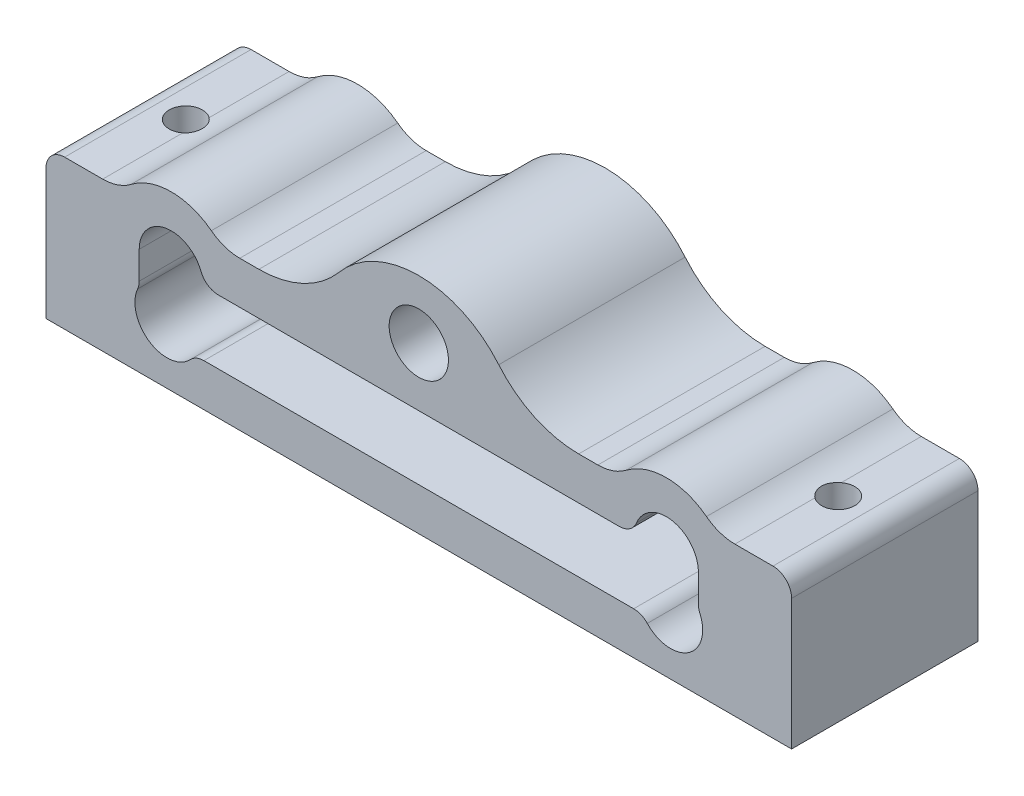
SolidWorks part; units mm, degrees
material "Delrin 2700 NC010, Low Viscosity Acetal Copolymer (SS)"
ref_plane "Front Plane" through (0, 0, 0) normal (0, 0, 1) x (1, 0, 0)
ref_plane "Top Plane" through (0, 0, 0) normal (0, 1, 0) x (1, 0, 0)
ref_plane "Right Plane" through (0, 0, 0) normal (1, 0, 0) x (0, 0, -1)
sketch "Sketch1" plane through (0, 0, 0) normal (0, 0, 1) x (1, 0, 0)
  line L0 (6.35, 5.08) -> (25.4, 5.08)
  line L9 (-25.4, -5.08) -> (25.4, -5.08)
  line L10 (-25.4, -5.08) -> (-25.4, 5.08)
  line L11 (-25.4, 5.08) -> (-6.35, 5.08)
  line L12 (25.4, -5.08) -> (25.4, 5.08)
  line L13 (-19.05, -2.1828) -> (19.05, -2.1828)
  line L14 (-19.05, -2.1828) -> (-19.05, 2.1828)
  line L15 (-19.05, 2.1828) -> (19.05, 2.1828)
  line L16 (19.05, -2.1828) -> (19.05, 2.1828)
  line L19 (-6.35, 5.08) -> (6.35, 5.08)
  point P9 (0, -2.1828)
  point P11 (19.05, 0)
  point P12 (25.4, 0)
  point P17 (0, 5.08)
  point P18 (0, -5.08)
  dimension "D1" = 50.8
  dimension "D2" = 10.16
  dimension "D3" = 38.1
  dimension "D4" = 4.3656
  dimension "D5" = 12.7
extrude "Boss-Extrude1" add sketch "Sketch1" along normal blind 12.7
sketch "Sketch7" plane through (0, 0, 12.7) normal (0, 0, 1) x (1, 0, 0)
  line L0 (19.05, 2.1828) -> (-19.05, 2.1828) construction
  line L1 (25.4, 5.08) -> (-25.4, 5.08) construction
  line L2 (-16.8672, 5.08) -> (-16.8672, 6.6675) construction
  line L3 (-20.2905, 5.08) -> (-13.4439, 5.08)
  circle A0 centre (-16.8672, 2.1828) radius 2.1828 construction
  arc A1 (-13.4439, 5.08) -> (-20.2905, 5.08) centre (-16.8672, 2.1828) ccw
  dimension "D1" = 4.3656
  dimension "D2" = 1.5875
extrude "Boss-Extrude3" add sketch "Sketch7" against normal up to surface (12.7 mm away) up to face at (0, 0, 0)
sketch "Sketch8" plane through (0, 0, 12.7) normal (0, 0, 1) x (1, 0, 0)
  line L0 (19.05, 2.1828) -> (-19.05, 2.1828) construction
  circle A0 centre (-16.8672, 2.1828) radius 2.1828
  dimension "D1" = 4.3656
extrude "Cut-Extrude1" cut sketch "Sketch8" against normal through all
sketch "Sketch11" plane through (0, 0, 12.7) normal (0, 0, 1) x (1, 0, 0)
  line L0 (-15.2693, -2.1828) -> (-19.05, 0) construction
  line L1 (-19.05, -2.1828) -> (19.05, -2.1828) construction
  line L2 (-19.05, 2.1828) -> (-19.05, -2.1828) construction
  circle A0 centre (-17.1596, -1.0914) radius 2.1828
  point P4 (-17.1596, -1.0914)
  dimension "D1" = 4.3656
extrude "Cut-Extrude2" cut sketch "Sketch11" against normal through all
fillet "Fillet1" radius 3.175 1 edges at (-13.4439, 5.08, 6.35)
mirror "Mirror1" about plane through (0, 0, 0) normal (1, 0, 0) of "Cut-Extrude2", "Cut-Extrude1"
mirror "Mirror2" about plane through (0, 0, 0) normal (1, 0, 0) of "Boss-Extrude3"
fillet "Fillet2" radius 3.175 1 edges at (13.4439, 5.08, 6.35)
hole_wizard "#4-40 Tapped Hole1" positions "Sketch2" profile "Sketch3" tap size "#4-40" standard "ANSI Inch" end condition through all
sketch "Sketch2" plane through (0, -5.08, 0) normal (0, -1, 0) x (-1, 0, 0)
  line L0 (-22.225, -6.35) -> (22.225, -6.35) construction
  line L2 (25.4, 0) -> (-25.4, 0) construction
  line L4 (25.4, -12.7) -> (-25.4, -12.7) construction
  point P0 (22.225, -6.35)
  point P2 (-22.225, -6.35)
  point P19 (0, 0)
  point P20 (0, -6.35)
  dimension "D1" = 44.45
  dimension "D2" = 6.35
cosmetic thread "Hole Thread4" parameters "D2"=2.8448
cosmetic thread "Hole Thread5" parameters "D2"=2.8448
sketch "Sketch3" plane through (-22.225, -5.08, 6.35) normal (1, 0, 0) x (0, 0, -1)
  line L0 (0, 0) -> (0, 11.7475)
  line L1 (0, 11.7475) -> (1.1303, 11.7475)
  line L2 (1.1303, 11.7475) -> (1.1303, 0)
  line L5 (1.1303, 0) -> (0, 0)
  line L11 (0, -6.35) -> (0, 107.95) construction
  dimension "Thru Tap Drill Dia." = 2.2606
  dimension "Thru Tap Drill Depth" = 11.7475
sketch "Sketch10" plane through (0, 0, 12.7) normal (0, 0, 1) x (1, 0, 0)
  line L0 (0, 10.16) -> (0, 2.1828) construction
  line L1 (14.6844, 2.1828) -> (-14.6844, 2.1828) construction
  line L2 (12.1982, 5.08) -> (-12.1982, 5.08) construction
  line L3 (-5.447, 7.62) -> (1.3402, 15.7087) construction
  line L5 (10.8941, 5.08) -> (-10.8941, 5.08)
  arc A0 (-14.1335, 5.738) -> (-12.1982, 5.08) centre (-12.1982, 8.255) ccw construction
  arc A1 (-14.1335, 5.738) -> (-12.1982, 5.08) centre (-12.1982, 8.255) ccw
  arc A3 (5.447, 7.62) -> (-5.447, 7.62) centre (0, 3.0494) ccw
  arc A4 (-5.447, 7.62) -> (-10.8941, 5.08) centre (-10.8941, 12.1906) cw
  arc A5 (5.447, 7.62) -> (10.8941, 5.08) centre (10.8941, 12.1906) ccw
  point P3 (0, 10.16)
  point P19 (0, 5.08)
  dimension "D1" = 5.08
  dimension "D2" = 50
extrude "Boss-Extrude4" add sketch "Sketch10" against normal up to surface (12.7 mm away) up to face at (0, 0.6188, 0)
hole_wizard "Tap Drill for #10-32 Tap1" positions "Sketch5" profile "Sketch6" hole size "#10-32" standard "ANSI Inch" end condition through all
sketch "Sketch5" plane through (0, 0, 12.7) normal (0, 0, 1) x (1, 0, 0)
  line L5 (0, 2.1828) -> (0, 10.16) construction
  line L6 (14.6844, 2.1828) -> (-14.6844, 2.1828) construction
  arc A0 (5.447, 7.62) -> (-5.447, 7.62) centre (0, 3.0494) ccw construction
  point P45 (0, 6.1714)
sketch "Sketch6" plane through (0, 6.1714, 12.7) normal (1, 0, 0) x (0, -1, 0)
  line L0 (0, 0) -> (0, 12.7)
  line L1 (0, 12.7) -> (2.0193, 12.7)
  line L2 (2.0193, 12.7) -> (2.0193, 0)
  line L5 (2.0193, 0) -> (0, 0)
  line L11 (0, -6.35) -> (0, 107.95) construction
  dimension "Thru Hole Dia." = 4.0386
  dimension "Thru Hole Depth" = 12.7
fillet "Fillet3" radius 1.27 6 edges at (14.6844, 2.1828, 6.35) (-14.6844, 2.1828, 6.35) (-19.05, 0, 6.35) (19.05, 0, 6.35) (15.2693, -2.1828, 6.35) (-15.2693, -2.1828, 6.35)
fillet "Fillet4" radius 1.27 2 edges at (25.4, 5.08, 6.35) (-25.4, 5.08, 6.35)
chamfer "Chamfer1" distance 0.254 14 edges at (-18.3628, -2.9127, 0) (-19.0772, 0.0379, 0) (-15.1455, -2.2875, 0) (-19.05, 1.241, 0) (0, -2.1828, 0) (-17.2759, 4.327, 0) (15.1455, -2.2875, 0) (-14.3704, 2.4025, 0) (18.3628, -2.9127, 0) (0, 2.1828, 0) (19.0772, 0.0379, 0) (14.3704, 2.4025, 0) (19.05, 1.241, 0) (17.2759, 4.327, 0)
sketch "Sketch12" [suppressed] plane through (0, 0, 12.7) normal (0, 0, 1) x (1, 0, 0)
  line L1 (-25.4, -5.08) -> (-38.1, -5.08)
  line L2 (-25.4, -5.08) -> (-25.4, 1.27)
  line L3 (-25.4, 1.27) -> (-38.1, 1.27)
  line L4 (-38.1, -5.08) -> (-38.1, 1.27)
  dimension "D1" = 12.7
  dimension "D2" = 6.35
extrude "Boss-Extrude5" [suppressed] add sketch "Sketch12" against normal blind 2.54
sketch "Sketch13" [suppressed] plane through (0, 0, 10.16) normal (0, 0, -1) x (-1, 0, 0)
  line L0 (38.1, -5.08) -> (25.4, -5.08) construction
  line L1 (38.1, 1.27) -> (31.75, 1.27)
  line L2 (38.1, 1.27) -> (38.1, -5.08)
  line L3 (38.1, -5.08) -> (31.75, -5.08)
  line L4 (31.75, 1.27) -> (31.75, -5.08)
  line L5 (25.4, 3.81) -> (25.4, -5.08) construction
  dimension "D1" = 6.35
extrude "Boss-Extrude6" [suppressed] add sketch "Sketch13" along normal up to surface (10.16 mm away)
hole_wizard "#8 Clearance Hole1" [suppressed] positions "Sketch14" profile "Sketch15" hole size "#8" standard "ANSI Inch"
sketch "Sketch14" plane through (0, 0, 0) normal (0, 0, -1) x (-1, 0, 0)
  point P0 (34.925, -1.905)
sketch "Sketch15" plane through (-34.925, -1.905, 0) normal (1, 0, 0) x (0, 1, 0)
  line L0 (0, 0) -> (0, 12.7)
  line L1 (0, 12.7) -> (2.2479, 12.7)
  line L2 (2.2479, 12.7) -> (2.2479, 0)
  line L5 (2.2479, 0) -> (0, 0)
  line L11 (0, -6.35) -> (0, 107.95) construction
  dimension "Thru Hole Dia." = 4.4958
  dimension "Thru Hole Depth" = 12.7
mirror "Mirror3" [suppressed] about plane through (0, 0, 0) normal (1, 0, 0)
sketch "Sketch16" [suppressed] plane through (0, 0, 10.16) normal (0, 0, -1) x (-1, 0, 0)
  line L0 (-25.4, 3.81) -> (-25.4, 3.175) construction
  line L1 (-25.4, -5.08) -> (-25.4, 3.81) construction
  line L2 (-31.75, 3.175) -> (-25.4, 3.175)
  arc A0 (-24.13, 5.08) -> (-25.4, 3.81) centre (-24.13, 3.81) ccw construction
  arc A1 (-24.13, 5.08) -> (-25.4, 3.81) centre (-24.13, 3.81) ccw
  arc A2 (-25.4, 3.175) -> (-31.75, 3.175) centre (-28.575, 3.175) cw
  line M2 (-25.4, 1.27) -> (-31.75, 1.27)
  dimension "D1" = 0.635
extrude "Cut-Extrude3" [suppressed] cut sketch "Sketch16" against normal through all contours A2 L2 M2 | A2 M2
mirror "Mirror4" [suppressed] about plane through (0, 0, 0) normal (1, 0, 0)
equation "\"atsFlapWidth\" = 1.5in"
equation "\"atsFlapThickness\" = 0.125in"
equation "\"D3@Sketch1\"=\"atsFlapWidth\""
equation "\"D1@Sketch1\"=\"atsFlapWidth\" + 0.5"
equation "\"D1@Sketch2\"=\"atsFlapWidth\"+0.25"
